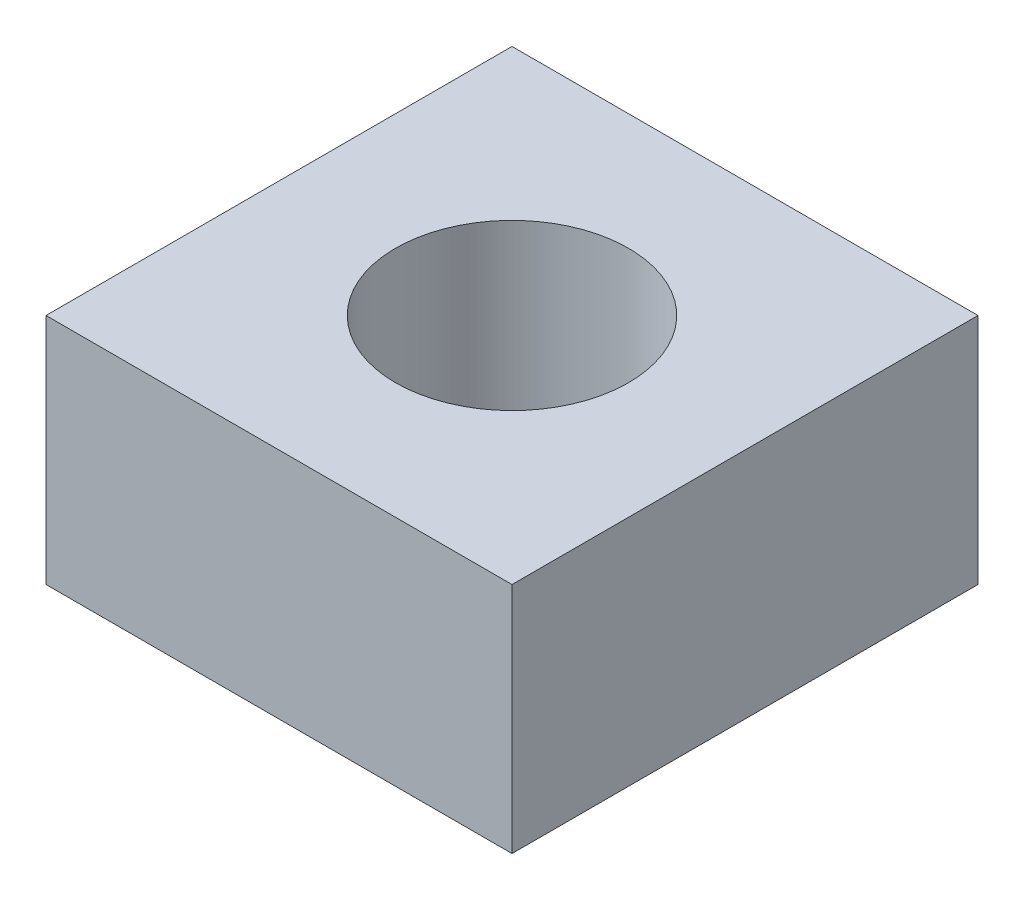
SolidWorks part; units mm, degrees
ref_plane "Plan de face" through (0, 0, 0) normal (0, 0, 1) x (1, 0, 0)
ref_plane "Plan de dessus" through (0, 0, 0) normal (0, 1, 0) x (1, 0, 0)
ref_plane "Plan de droite" through (0, 0, 0) normal (1, 0, 0) x (0, 0, -1)
sketch "Sketch1" plane through (0, 0, 0) normal (0, 1, 0) x (1, 0, 0)
  line L1 (3, -3) -> (-3, -3)
  line L2 (3, -3) -> (3, 3)
  line L3 (3, 3) -> (-3, 3)
  line L4 (-3, -3) -> (-3, 3)
  line L5 (3, -3) -> (-3, 3) construction
  line L6 (3, 3) -> (-3, -3) construction
  point P0 (0, 0)
  dimension "D1" = 6
  dimension "D2" = 6
extrude "Boss-Extrude1" add sketch "Sketch1" along normal blind 3
sketch "Sketch2" plane through (0, 3, 0) normal (0, 1, 0) x (-1, 0, 0)
  circle A0 centre (0, 0) radius 1.5
extrude "Cut-Extrude1" cut sketch "Sketch2" against normal through all
